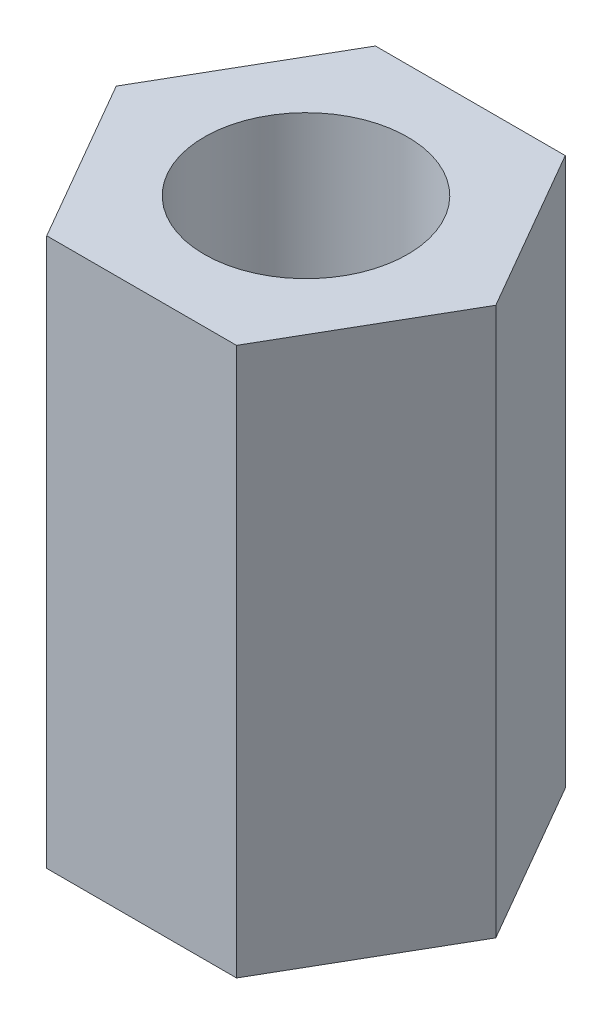
SolidWorks part; units mm, degrees
ref_plane "Front Plane" through (0, 0, 0) normal (0, 0, 1) x (1, 0, 0)
ref_plane "Top Plane" through (0, 0, 0) normal (0, 1, 0) x (1, 0, 0)
ref_plane "Right Plane" through (0, 0, 0) normal (1, 0, 0) x (0, 0, -1)
sketch "Sketch1" plane through (0, 0, 0) normal (0, 1, 0) x (1, 0, 0)
  line L1 (2.7496, 0) -> (1.3748, 2.3813)
  line L2 (1.3748, 2.3813) -> (-1.3748, 2.3813)
  line L3 (-1.3748, 2.3813) -> (-2.7496, 0)
  line L4 (-2.7496, 0) -> (-1.3748, -2.3813)
  line L5 (-1.3748, -2.3813) -> (1.3748, -2.3813)
  line L6 (1.3748, -2.3813) -> (2.7496, 0)
  circle A0 centre (0, 0) radius 2.3813 construction
  dimension "D1" = 4.7625
extrude "Boss-Extrude1" add sketch "Sketch1" along normal blind 7.9375
hole_wizard "#97 (0.0059) Diameter Hole1" positions "Sketch3" profile "Sketch2" hole size "#97" standard "ANSI Inch"
sketch "Sketch3" plane through (0, 7.9375, 0) normal (0, 1, 0) x (1, 0, 0)
  point P0 (0, 0)
sketch "Sketch2" plane through (0, 7.9375, 0) normal (1, 0, 0) x (0, 0, 1)
  line L0 (0, 0) -> (0, 26.2852)
  line L1 (0, 26.2852) -> (1.4732, 25.4)
  line L2 (1.4732, 25.4) -> (1.4732, 0)
  line L5 (1.4732, 0) -> (0, 0)
  line L10 (0, 26.2852) -> (-1.4732, 25.4) construction
  line L11 (0, -6.35) -> (0, 107.95) construction
  dimension "Hole Dia." = 2.9464
  dimension "Hole Depth" = 25.4
  dimension "Drill Angle" = 118
